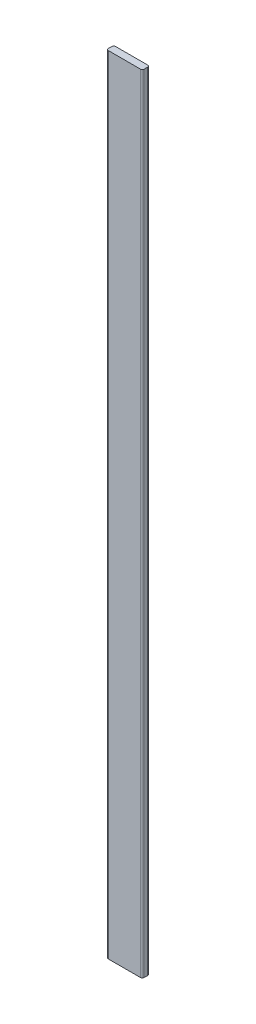
SolidWorks part; units mm, degrees
material "Сосна"
ref_plane "Спереди" through (0, 0, 0) normal (0, 0, 1) x (1, 0, 0)
ref_plane "Сверху" through (0, 0, 0) normal (0, 1, 0) x (1, 0, 0)
ref_plane "Справа" through (0, 0, 0) normal (1, 0, 0) x (0, 0, -1)
sketch "Эскиз1" plane through (0, 0, 0) normal (0, 0, 1) x (1, 0, 0)
  line L1 (-381.5789, 2127.6316) -> (-281.5789, 2127.6316)
  line L2 (-381.5789, 2127.6316) -> (-381.5789, -72.3684)
  line L3 (-381.5789, -72.3684) -> (-281.5789, -72.3684)
  line L4 (-281.5789, 2127.6316) -> (-281.5789, -72.3684)
  dimension "D1" = 100
  dimension "D2" = 2200
extrude "Бобышка-Вытянуть1" add sketch "Эскиз1" along normal blind 20
fillet "Скругление1" radius 5 4 edges at (-381.5789, 1027.6316, 0) (-381.5789, 1027.6316, 20) (-281.5789, 1027.6316, 0) (-281.5789, 1027.6316, 20)
